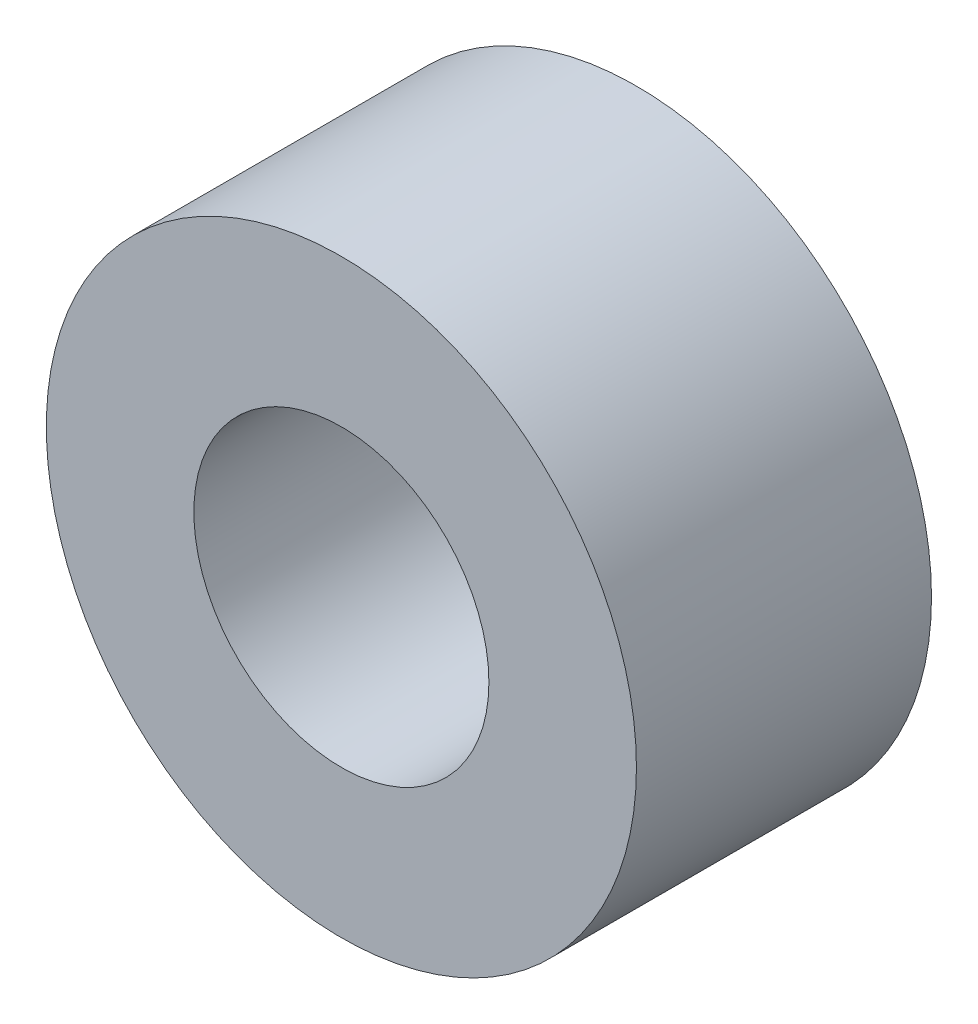
SolidWorks part; units mm, degrees
material "AISI 4340 Steel, normalized"
ref_plane "Front Plane" through (0, 0, 0) normal (0, 0, 1) x (1, 0, 0)
ref_plane "Top Plane" through (0, 0, 0) normal (0, 1, 0) x (1, 0, 0)
ref_plane "Right Plane" through (0, 0, 0) normal (1, 0, 0) x (0, 0, -1)
sketch "Sketch1" plane through (0, 0, 0) normal (0, 0, 1) x (1, 0, 0)
  circle A0 centre (0, 0) radius 8
  circle A1 centre (0, 0) radius 4
extrude "Washer_Envelope" add sketch "Sketch1" along normal blind 8
